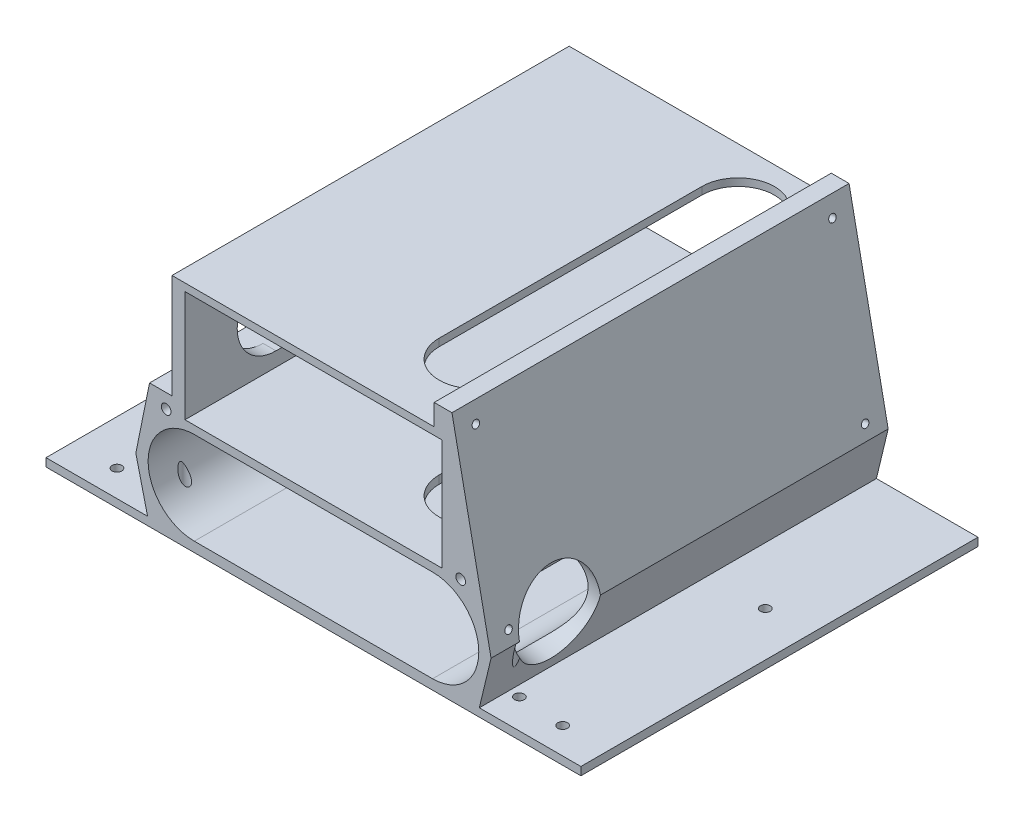
SolidWorks part; units mm, degrees
ref_plane "Plan de face" through (0, 0, 0) normal (0, 0, 1) x (1, 0, 0)
ref_plane "Plan de dessus" through (0, 0, 0) normal (0, 1, 0) x (1, 0, 0)
ref_plane "Plan de droite" through (0, 0, 0) normal (1, 0, 0) x (0, 0, -1)
sketch "Esquisse1" plane through (0, 0, 0) normal (0, 0, 1) x (1, 0, 0)
  line L1 (-56.0863, -46.0305) -> (56.0863, -46.0305)
  line L2 (-56.0863, -46.0305) -> (-56.0863, 46.0305)
  line L3 (-56.0863, 46.0305) -> (56.0863, 46.0305)
  line L4 (56.0863, -46.0305) -> (56.0863, 46.0305)
  line L5 (-56.0863, -46.0305) -> (56.0863, 46.0305) construction
  line L6 (-56.0863, 46.0305) -> (56.0863, -46.0305) construction
  point P0 (0, 0)
extrude "Boss.-Extru.1" add sketch "Esquisse1" along normal blind 98
sketch "Esquisse2" plane through (0, 0, 98) normal (0, 0, 1) x (1, 0, 0)
  line L0 (0, 46.0305) -> (0, -46.0305) construction
  line L1 (56.0863, 46.0305) -> (-56.0863, 46.0305) construction
  line L2 (-56.0863, -46.0305) -> (56.0863, -46.0305) construction
  line L4 (-31.7, 16.7912) -> (31.7, 16.7912)
  line L5 (-31.7, 16.7912) -> (-31.7, 44.1912)
  line L6 (-31.7, 44.1912) -> (31.7, 44.1912)
  line L7 (31.7, 16.7912) -> (31.7, 44.1912)
  line L8 (-31.7, 16.7912) -> (31.7, 44.1912) construction
  line L9 (-31.7, 44.1912) -> (31.7, 16.7912) construction
  point P6 (0, 30.4912)
  dimension "D1" = 63.4
  dimension "D2" = 27.4
extrude "Enlèv. mat.-Extru.1" cut sketch "Esquisse2" against normal through all
sketch "Esquisse3" plane through (0, 0, 98) normal (0, 0, 1) x (1, 0, 0)
  line L0 (-29.4, 3.3912) -> (29.4, 3.3912) construction
  line L1 (-29.4, 14.7912) -> (29.4, 14.7912)
  line L2 (-29.4, -8.0088) -> (29.4, -8.0088)
  line L3 (-31.7, 16.7912) -> (31.7, 16.7912) construction
  line L4 (0, 46.0305) -> (0, -46.0305) construction
  line L5 (56.0863, 46.0305) -> (-56.0863, 46.0305) construction
  line L6 (-56.0863, -46.0305) -> (56.0863, -46.0305) construction
  arc A0 (-29.4, 14.7912) -> (-29.4, -8.0088) centre (-29.4, 3.3912) ccw
  arc A1 (29.4, -8.0088) -> (29.4, 14.7912) centre (29.4, 3.3912) ccw
  point P2 (0, 3.3912)
  dimension "D1" = 2
  dimension "D2" = 0
extrude "Enlèv. mat.-Extru.2" cut sketch "Esquisse3" against normal through all
sketch "Esquisse8" plane through (0, 0, 0) normal (0, 0, -1) x (-1, 0, 0)
  line L0 (40.45, -43.7588) -> (40.45, -46.0305) construction
  line L1 (56.0863, -46.0305) -> (-56.0863, -46.0305) construction
  line L2 (40.45, -10.4588) -> (43.8315, 3.5912) construction
  line L3 (43.8315, 3.5912) -> (40.45, 20.287) construction
  line L4 (40.45, 20.287) -> (34.9042, 20.287) construction
  line L5 (34.9042, 20.287) -> (34.9042, 46.0305) construction
  line L6 (-56.0863, 46.0305) -> (56.0863, 46.0305) construction
  line L7 (40.45, -46.0305) -> (40.45, -10.4588)
  line L8 (40.45, -10.4588) -> (43.8315, 3.5912)
  line L9 (43.8315, 3.5912) -> (40.45, 20.287)
  line L10 (40.45, 20.287) -> (34.9042, 20.287)
  line L11 (34.9042, 20.287) -> (34.9042, 46.0305)
  line L12 (0, -46.0305) -> (0, 46.0305) construction
  line L13 (-40.45, -46.0305) -> (-40.45, -10.4588)
  line L14 (-40.45, -10.4588) -> (-43.8315, 3.5912)
  line L15 (-43.8315, 3.5912) -> (-40.45, 20.287)
  line L18 (-35.236, 46.0305) -> (-56.0863, 46.0305)
  line L19 (-56.0863, 46.0305) -> (-56.0863, -46.0305)
  line L20 (-56.0863, -46.0305) -> (-40.45, -46.0305)
  line L21 (40.45, -46.0305) -> (56.0863, -46.0305)
  line L22 (56.0863, -46.0305) -> (56.0863, 46.0305)
  line L23 (56.0863, 46.0305) -> (34.9042, 46.0305)
  line L24 (-40.45, 20.287) -> (-35.236, 46.0305)
  circle A0 centre (36.3424, 16.7291) radius 1.2
  circle A1 centre (-36.3424, 16.7291) radius 1.2
extrude "Enlèv. mat.-Extru.5" cut sketch "Esquisse8" against normal through all
sketch "Esquisse13" plane through (0, 46.0305, 0) normal (0, 1, 0) x (1, 0, 0)
  line L0 (20.43, -13.6311) -> (20.43, -78.4445) construction
  line L1 (29.4015, -13.6311) -> (29.4015, -78.4445)
  line L2 (11.4585, -13.6311) -> (11.4585, -78.4445)
  arc A0 (29.4015, -13.6311) -> (11.4585, -13.6311) centre (20.43, -13.6311) ccw
  arc A1 (11.4585, -78.4445) -> (29.4015, -78.4445) centre (20.43, -78.4445) ccw
  point P2 (20.43, -46.0378)
extrude "Enlèv. mat.-Extru.10" cut sketch "Esquisse13" against normal blind 36
sketch "Esquisse14" plane through (0, 0, 0) normal (0, 0, -1) x (-1, 0, 0)
  line L0 (-35.236, 46.0305) -> (-34.1813, 51.2377)
  line L1 (-34.1813, 51.2377) -> (-29.7868, 51.2377)
  line L2 (-29.7868, 51.2377) -> (-29.7868, 46.0305)
  line L3 (-35.236, 46.0305) -> (34.9042, 46.0305) construction
  line L4 (-29.7868, 46.0305) -> (-35.236, 46.0305)
extrude "Boss.-Extru.2" add sketch "Esquisse14" against normal through all
sketch "Esquisse15" plane through (42.803, 8.6693, 0) normal (0.9801, 0.1985, 0) x (0, 0, -1)
  circle A0 centre (-5.0126, -1.8311) radius 0.9
  circle A1 centre (-5.0126, 38.8689) radius 0.9
  circle A2 centre (-93.0126, -1.8311) radius 0.9
  circle A3 centre (-93.0126, 38.8689) radius 0.9
extrude "Enlèv. mat.-Extru.11" cut sketch "Esquisse15" against normal blind 5
sketch "Esquisse17" plane through (-34.9042, 0, 0) normal (-1, 0, 0) x (0, 0, 1)
  line L0 (11.8912, 29.8641) -> (75.5405, 29.8641) construction
  line L1 (11.8912, 39.4412) -> (75.5405, 39.4412)
  line L2 (11.8912, 20.287) -> (75.5405, 20.287)
  line L3 (98, 20.287) -> (0, 20.287) construction
  arc A0 (11.8912, 39.4412) -> (11.8912, 20.287) centre (11.8912, 29.8641) ccw
  arc A1 (75.5405, 20.287) -> (75.5405, 39.4412) centre (75.5405, 29.8641) ccw
  point P2 (43.7159, 29.8641)
extrude "Enlèv. mat.-Extru.13" cut sketch "Esquisse17" against normal blind 33
sketch "Esquisse18" plane through (40.6145, -9.7751, 0) normal (0.9722, -0.234, 0) x (0, 0, -1)
  line L0 (-98, 13.748) -> (0, 13.748) construction
  line L1 (-98, -0.7032) -> (-98, 13.748) construction
  circle A0 centre (-81, 13.748) radius 10
  dimension "D1" = 17
extrude "Enlèv. mat.-Extru.14" cut sketch "Esquisse18" against normal blind 7
sketch "Esquisse19" plane through (0, 0, 0) normal (0, 0, -1) x (-1, 0, 0)
  line L1 (-40.45, -10.4588) -> (40.45, -10.4588)
  line L2 (-40.45, -10.4588) -> (-40.45, -46.0305)
  line L3 (-40.45, -46.0305) -> (40.45, -46.0305)
  line L4 (40.45, -10.4588) -> (40.45, -46.0305)
extrude "Enlèv. mat.-Extru.15" cut sketch "Esquisse19" against normal through all
sketch "Esquisse21" plane through (0, -10.4588, 0) normal (0, -1, 0) x (1, 0, 0)
  line L0 (-40.45, 98) -> (40.45, 98)
  line L1 (40.45, 98) -> (66, 98)
  line L2 (40.45, 98) -> (40.45, 0) construction
  line L3 (40.45, 0) -> (66, 0)
  line L4 (66, 98) -> (66, 0)
  line L5 (-40.45, 98) -> (-66, 98)
  line L6 (-40.45, 98) -> (-40.45, 0) construction
  line L7 (-40.45, 0) -> (-66, 0)
  line L8 (-66, 98) -> (-66, 0)
  line L9 (-40.45, 0) -> (40.45, 0)
  dimension "D1" = 25.55
  dimension "D2" = 25.55
extrude "Boss.-Extru.3" add sketch "Esquisse21" against normal blind 2
sketch "Esquisse22" plane through (0, -10.4588, 0) normal (0, -1, 0) x (1, 0, 0)
  circle A0 centre (43.5376, 90.7126) radius 1.2
  circle A1 centre (55, 91.4926) radius 1.2
  circle A2 centre (37.3176, 42.5126) radius 1.2
  circle A3 centre (55, 41.4926) radius 1.2
  circle A4 centre (-55, 41.4926) radius 1.2
  circle A5 centre (-37.9224, 42.5126) radius 1.2
  circle A6 centre (-55, 91.4926) radius 1.2
  circle A7 centre (-39.0655, 90.7126) radius 1.2
extrude "Enlèv. mat.-Extru.16" cut sketch "Esquisse22" against normal blind 14
